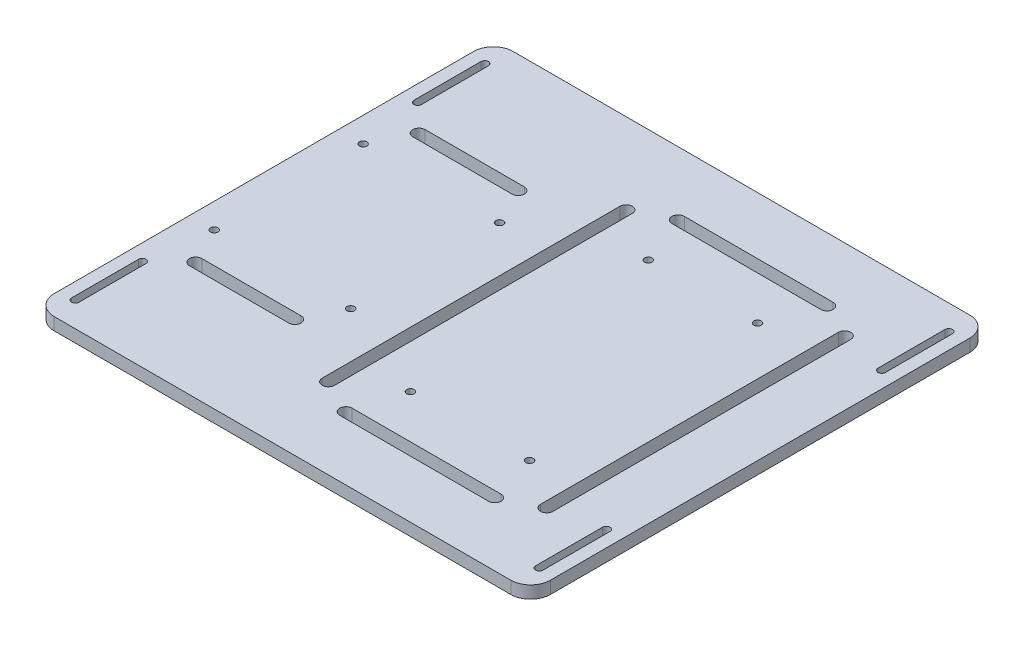
SolidWorks part; units mm, degrees
ref_plane "Front Plane" through (0, 0, 0) normal (0, 0, 1) x (1, 0, 0)
ref_plane "Top Plane" through (0, 0, 0) normal (0, 1, 0) x (1, 0, 0)
ref_plane "Right Plane" through (0, 0, 0) normal (1, 0, 0) x (0, 0, -1)
sketch "Sketch2" plane through (0, 0, 0) normal (0, 1, 0) x (1, 0, 0)
  line L0 (-93.5, 55.5) -> (-93.5, 82.5) construction
  line L1 (-100, -92.5) -> (100, -92.5)
  line L2 (-100, -92.5) -> (-100, 92.5)
  line L3 (-100, 92.5) -> (100, 92.5)
  line L4 (100, -92.5) -> (100, 92.5)
  line L5 (-100, -92.5) -> (100, 92.5) construction
  line L6 (-100, 92.5) -> (100, -92.5) construction
  line L7 (-95, 55.5) -> (-95, 82.5)
  line L8 (-92, 55.5) -> (-92, 82.5)
  line L9 (-100, 0) -> (100, 0) construction
  line L10 (100, 0) -> (0, 92.5) construction
  line L11 (0, 92.5) -> (0, -92.5) construction
  line L12 (93.5, 55.5) -> (93.5, 82.5) construction
  line L13 (95, 55.5) -> (95, 82.5)
  line L14 (92, 55.5) -> (92, 82.5)
  line L15 (93.5, -55.5) -> (93.5, -82.5) construction
  line L16 (95, -55.5) -> (95, -82.5)
  line L17 (92, -55.5) -> (92, -82.5)
  line L18 (-93.5, -55.5) -> (-93.5, -82.5) construction
  line L19 (-95, -55.5) -> (-95, -82.5)
  line L20 (-92, -55.5) -> (-92, -82.5)
  arc A0 (-95, 55.5) -> (-92, 55.5) centre (-93.5, 55.5) ccw
  arc A1 (-92, 82.5) -> (-95, 82.5) centre (-93.5, 82.5) ccw
  arc A2 (95, 55.5) -> (92, 55.5) centre (93.5, 55.5) cw
  arc A3 (92, 82.5) -> (95, 82.5) centre (93.5, 82.5) cw
  arc A4 (95, -55.5) -> (92, -55.5) centre (93.5, -55.5) ccw
  arc A5 (92, -82.5) -> (95, -82.5) centre (93.5, -82.5) ccw
  arc A6 (-95, -55.5) -> (-92, -55.5) centre (-93.5, -55.5) cw
  arc A7 (-92, -82.5) -> (-95, -82.5) centre (-93.5, -82.5) cw
  point P0 (0, 0)
  point P8 (-93.5, 69)
  point P19 (93.5, 69)
  point P26 (93.5, -69)
  point P33 (-93.5, -69)
  dimension "D4" = 1.5
  dimension "D1" = 200
  dimension "D2" = 185
  dimension "D3" = 27
  dimension "D5" = 5
  dimension "D6" = 10
extrude "Boss-Extrude1" add sketch "Sketch2" along normal blind 5
sketch "Sketch3" plane through (0, 5, 0) normal (0, 1, 0) x (1, 0, 0)
  line L0 (-100, 0) -> (100, 0) construction
  line L1 (-100, 92.5) -> (-100, -92.5) construction
  line L2 (100, -92.5) -> (100, 92.5) construction
  line L3 (100, 0) -> (0, -92.5) construction
  line L4 (-100, -92.5) -> (100, -92.5) construction
  line L5 (0, -92.5) -> (0, 92.5) construction
  line L6 (100, 92.5) -> (-100, 92.5) construction
  line L7 (-62.5, -35) -> (-62.5, 55.3864) construction
  line L8 (-30, -35) -> (-95, -35)
  line L9 (-30, -35) -> (-30, 35)
  line L10 (-30, 35) -> (-95, 35)
  line L11 (-95, -35) -> (-95, 35)
  line L12 (-30, -35) -> (-95, 35) construction
  line L13 (-30, 35) -> (-95, -35) construction
  line L14 (-82.5, 45) -> (-42.5, 45) construction
  line L15 (-82.5, 47.5) -> (-42.5, 47.5)
  line L16 (-82.5, 42.5) -> (-42.5, 42.5)
  line L17 (-82.5, -45) -> (-42.5, -45) construction
  line L18 (-82.5, -47.5) -> (-42.5, -47.5)
  line L19 (-82.5, -42.5) -> (-42.5, -42.5)
  circle A0 centre (-90, -30) radius 1.5
  circle A1 centre (-90, 30) radius 1.5
  circle A2 centre (-35, 30) radius 1.5
  circle A3 centre (-35, -30) radius 1.5
  arc A4 (-82.5, 47.5) -> (-82.5, 42.5) centre (-82.5, 45) ccw
  arc A5 (-42.5, 42.5) -> (-42.5, 47.5) centre (-42.5, 45) ccw
  arc A6 (-82.5, -47.5) -> (-82.5, -42.5) centre (-82.5, -45) cw
  arc A7 (-42.5, -42.5) -> (-42.5, -47.5) centre (-42.5, -45) cw
  point P9 (-62.5, 0)
  point P29 (-62.5, 45)
  point P36 (-62.5, -45)
  dimension "D4" = 3
  dimension "D8" = 2.5
  dimension "D1" = 65
  dimension "D2" = 70
  dimension "D3" = 5
  dimension "D5" = 5
  dimension "D6" = 5
  dimension "D7" = 40
  dimension "D9" = 10
extrude "Cut-Extrude1" cut sketch "Sketch3" against normal through all contours L16 A5 L15 A4 | A7 L19 A6 L18 | A0 | A1 | A3 | A2
sketch "Sketch4" plane through (0, 5, 0) normal (0, 1, 0) x (1, 0, 0)
  line L0 (-100, 0) -> (100, 0) construction
  line L1 (-100, 92.5) -> (-100, -92.5) construction
  line L2 (100, -92.5) -> (100, 92.5) construction
  line L3 (30, 92.5) -> (30, -92.5) construction
  line L4 (100, 92.5) -> (-100, 92.5) construction
  line L5 (-100, -92.5) -> (100, -92.5) construction
  line L6 (74, -60) -> (74, 60) construction
  line L7 (71.5, -60) -> (71.5, 60)
  line L8 (76.5, -60) -> (76.5, 60)
  line L9 (-14, -60) -> (-14, 60) construction
  line L10 (-16.5, -60) -> (-16.5, 60)
  line L11 (-11.5, -60) -> (-11.5, 60)
  line L12 (0, 66.935) -> (60, 66.935) construction
  line L13 (0, 69.435) -> (60, 69.435)
  line L14 (0, 64.435) -> (60, 64.435)
  line L15 (0, -66.935) -> (60, -66.935) construction
  line L16 (0, -69.435) -> (60, -69.435)
  line L17 (0, -64.435) -> (60, -64.435)
  circle A0 centre (8, 46.935) radius 1.5
  circle A1 centre (52, 46.935) radius 1.5
  circle A2 centre (6, -46.935) radius 1.5
  circle A3 centre (54, -46.935) radius 1.5
  arc A4 (71.5, -60) -> (76.5, -60) centre (74, -60) ccw
  arc A5 (76.5, 60) -> (71.5, 60) centre (74, 60) ccw
  arc A6 (-16.5, -60) -> (-11.5, -60) centre (-14, -60) ccw
  arc A7 (-11.5, 60) -> (-16.5, 60) centre (-14, 60) ccw
  arc A8 (0, 69.435) -> (0, 64.435) centre (0, 66.935) ccw
  arc A9 (60, 64.435) -> (60, 69.435) centre (60, 66.935) ccw
  arc A10 (0, -69.435) -> (0, -64.435) centre (0, -66.935) cw
  arc A11 (60, -64.435) -> (60, -69.435) centre (60, -66.935) cw
  point P22 (74, 0)
  point P29 (-14, 0)
  point P37 (30, 66.935)
  point P44 (30, -66.935)
  point P49 (0, 0)
  dimension "D1" = 3
  dimension "D4" = 3
  dimension "D7" = 46.935
  dimension "D8" = 2.5
  dimension "D12" = 2.5
  dimension "D15" = 2.5
  dimension "D2" = 70
  dimension "D3" = 44
  dimension "D5" = 48
  dimension "D6" = 93.87
  dimension "D9" = 120
  dimension "D10" = 20
  dimension "D11" = 120
  dimension "D13" = 20
  dimension "D14" = 60
  dimension "D16" = 20
extrude "Cut-Extrude3" cut sketch "Sketch4" against normal through all
fillet "Fillet1" radius 8 4 edges at (100, 2.5, -92.5) (100, 2.5, 92.5) (-100, 2.5, -92.5) (-100, 2.5, 92.5)
